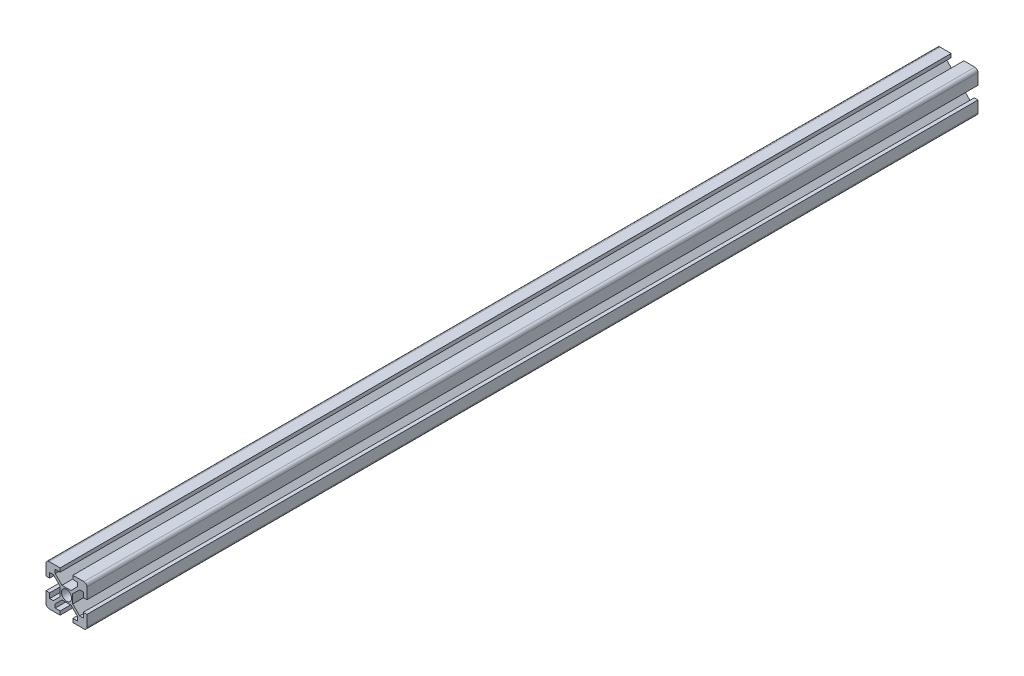
SolidWorks part; units mm, degrees
ref_plane "前视基准面" through (0, 0, 0) normal (0, 0, 1) x (1, 0, 0)
ref_plane "上视基准面" through (0, 0, 0) normal (0, 1, 0) x (1, 0, 0)
ref_plane "右视基准面" through (0, 0, 0) normal (1, 0, 0) x (0, 0, -1)
sketch "草图1" plane through (0, 0, 0) normal (0, 0, 1) x (1, 0, 0)
  line L0 (-10, -3.1) -> (-8.2, -3.1)
  line L1 (-8.5, 10) -> (8.5, 10)
  line L2 (-10, 8.5) -> (-10, -8.5)
  line L3 (-8.5, -10) -> (8.5, -10)
  line L4 (10, 8.5) -> (10, -8.5)
  line L5 (-10, 10) -> (10, -10) construction
  line L6 (-10, -10) -> (10, 10) construction
  line L7 (-3.0541, 3.1) -> (3.0541, 3.1)
  line L8 (-3.0541, 3.1) -> (-3.0541, -3.1)
  line L9 (-3.0541, -3.1) -> (3.0541, -3.1)
  line L10 (3.0541, 3.1) -> (3.0541, -3.1)
  line L11 (-3.0541, 3.1) -> (3.0541, -3.1) construction
  line L12 (-3.0541, -3.1) -> (3.0541, 3.1) construction
  line L13 (-8.2, -3.1) -> (-8.2, -5.5)
  line L14 (-8.2, -5.5) -> (-6.3971, -5.5)
  line L15 (-6.3971, -5.5) -> (-3.0541, -2.1571)
  line L16 (-5.5, 6.3971) -> (-2.1571, 3.0541)
  line L17 (-5.5, 8.2) -> (-5.5, 6.3971)
  line L18 (-3.1, 8.2) -> (-5.5, 8.2)
  line L19 (-3.1, 10) -> (-3.1, 8.2)
  line L20 (6.3971, 5.5) -> (3.0541, 2.1571)
  line L21 (8.2, 5.5) -> (6.3971, 5.5)
  line L22 (8.2, 3.1) -> (8.2, 5.5)
  line L23 (10, 3.1) -> (8.2, 3.1)
  line L24 (5.5, -6.3971) -> (2.1571, -3.0541)
  line L25 (5.5, -8.2) -> (5.5, -6.3971)
  line L26 (3.1, -8.2) -> (5.5, -8.2)
  line L27 (3.1, -10) -> (3.1, -8.2)
  line L28 (-3.1, -10) -> (-3.1, -8.2)
  line L29 (-3.1, -8.2) -> (-5.5, -8.2)
  line L30 (-5.5, -8.2) -> (-5.5, -6.3971)
  line L31 (-5.5, -6.3971) -> (-2.1571, -3.0541)
  line L32 (-8.2, 5.5) -> (-6.3971, 5.5)
  line L33 (-6.3971, 5.5) -> (-3.0541, 2.1571)
  line L34 (-8.2, 3.1) -> (-8.2, 5.5)
  line L35 (-10, 3.1) -> (-8.2, 3.1)
  line L36 (5.5, 8.2) -> (5.5, 6.3971)
  line L37 (5.5, 6.3971) -> (2.1571, 3.0541)
  line L38 (3.1, 8.2) -> (5.5, 8.2)
  line L39 (3.1, 10) -> (3.1, 8.2)
  line L40 (8.2, -5.5) -> (6.3971, -5.5)
  line L41 (6.3971, -5.5) -> (3.0541, -2.1571)
  line L42 (8.2, -3.1) -> (8.2, -5.5)
  line L43 (10, -3.1) -> (8.2, -3.1)
  circle A0 centre (0, 0) radius 2.5
  arc A1 (-10, 8.5) -> (-8.5, 10) centre (-8.5, 8.5) cw
  arc A2 (-10, -8.5) -> (-8.5, -10) centre (-8.5, -8.5) ccw
  arc A3 (8.5, 10) -> (10, 8.5) centre (8.5, 8.5) cw
  arc A4 (10, -8.5) -> (8.5, -10) centre (8.5, -8.5) cw
  point P0 (0, 0)
  point P20 (0, 0)
  point P26 (0, 0)
  point P32 (0, 0)
  point P38 (0, 0)
  point P60 (0, 0)
  dimension "D1" = 4
  dimension "D3" = 1.5
  dimension "D4" = 1.5
  dimension "D5" = 1.5
  dimension "D2" = 4
extrude "凸台-拉伸1" add sketch "草图1" along normal blind 435
